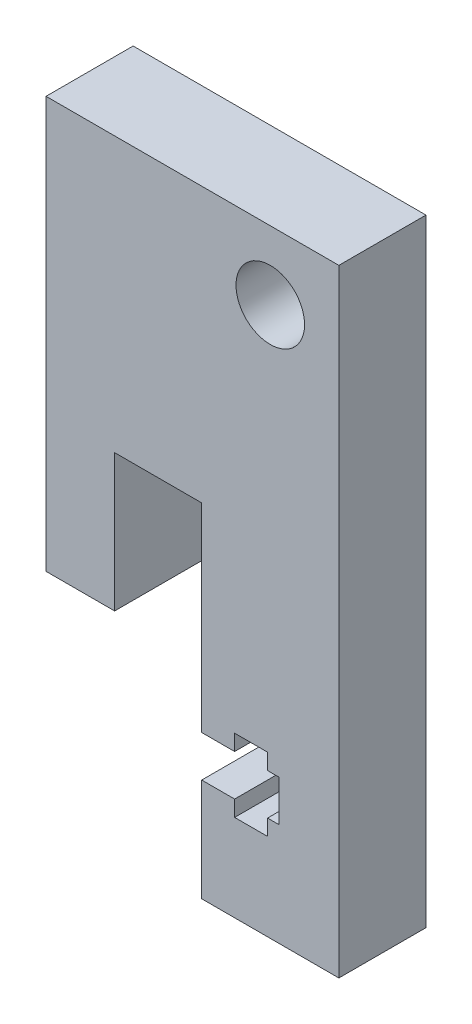
SolidWorks part; units mm, degrees
ref_plane "Front Plane" through (0, 0, 0) normal (0, 0, 1) x (1, 0, 0)
ref_plane "Top Plane" through (0, 0, 0) normal (0, 1, 0) x (1, 0, 0)
ref_plane "Right Plane" through (0, 0, 0) normal (1, 0, 0) x (0, 0, -1)
sketch "Sketch1" plane through (0, 0, 0) normal (0, 0, 1) x (1, 0, 0)
  line L1 (8.5406, 34.2167) -> (8.5406, -10.7833)
  line L2 (8.5406, -10.7833) -> (-1.4594, -10.7833)
  line L3 (-1.4594, -10.7833) -> (-1.4594, 14.2167)
  line L4 (-1.4594, 14.2167) -> (-7.8094, 14.2167)
  line L5 (-7.8094, 14.2167) -> (-7.8094, 4.2167)
  line L6 (-7.8094, 4.2167) -> (-12.8094, 4.2167)
  line L7 (-12.8094, 4.2167) -> (-12.8094, 34.2167)
  line L9 (-12.8094, 34.2167) -> (8.5406, 34.2167)
  line L10 (-1.4594, -0.2833) -> (0.9406, -0.2833)
  line L11 (0.9406, -0.2833) -> (0.9406, 0.8767)
  line L12 (0.9406, 0.8767) -> (3.3406, 0.8767)
  line L13 (3.3406, 0.8767) -> (3.3406, -0.2833)
  line L14 (3.3406, -0.2833) -> (4.1906, -0.2833)
  line L15 (4.1906, -0.2833) -> (4.1906, -3.2833)
  line L16 (4.1906, -3.2833) -> (3.3406, -3.2833)
  line L17 (3.3406, -3.2833) -> (3.3406, -4.4433)
  line L18 (3.3406, -4.4433) -> (0.9406, -4.4433)
  line L19 (0.9406, -4.4433) -> (0.9406, -3.2833)
  line L20 (0.9406, -3.2833) -> (-1.4594, -3.2833)
  circle A0 centre (3.5406, 29.2167) radius 2.5
  point P20 (4.1906, -1.7833)
  dimension "D15" = 5
  dimension "D1" = 10
  dimension "D2" = 3
  dimension "D3" = 5.32
  dimension "D4" = 2.66
  dimension "D5" = 2.4
  dimension "D6" = 5.65
  dimension "D7" = 7.5
  dimension "D8" = 45
  dimension "D9" = 2.4
  dimension "D10" = 6.35
  dimension "D11" = 5
  dimension "D12" = 10
  dimension "D13" = 25
  dimension "D14" = 5
  dimension "D16" = 5
extrude "Boss-Extrude1" add sketch "Sketch1" along normal blind 6.35 contours L19 L20 L3 L2 L1 L9 L7 L6 L5 L4 L10 L11 L12 L13 L14 L15 L16 L17 L18 A0
